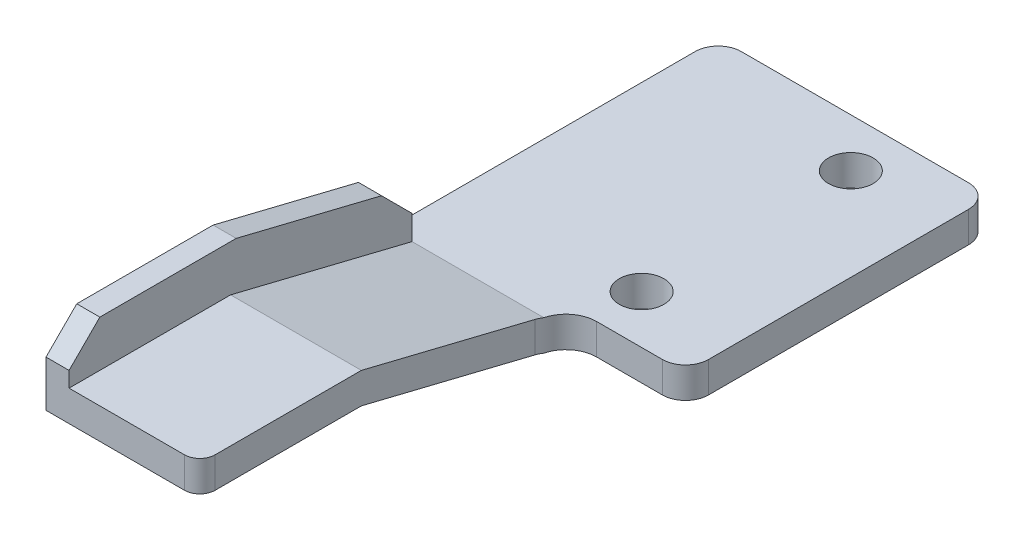
SolidWorks part; units mm, degrees
ref_plane "Front Plane" through (0, 0, 0) normal (0, 0, 1) x (1, 0, 0)
ref_plane "Top Plane" through (0, 0, 0) normal (0, 1, 0) x (1, 0, 0)
ref_plane "Right Plane" through (0, 0, 0) normal (1, 0, 0) x (0, 0, -1)
sketch "Sketch1" plane through (0, 0, 0) normal (0, 1, 0) x (1, 0, 0)
  line L0 (2.885, 6.8) -> (2.885, -6.8) construction
  line L1 (8.885, 9.95) -> (-8.885, 9.95)
  line L2 (8.885, 9.95) -> (8.885, -9.95)
  line L3 (8.885, -9.95) -> (-8.885, -9.95)
  line L4 (-8.885, 9.95) -> (-8.885, -9.95)
  line L5 (8.885, 9.95) -> (-8.885, -9.95) construction
  line L6 (8.885, -9.95) -> (-8.885, 9.95) construction
  circle A0 centre (2.885, 6.8) radius 1.45
  circle A1 centre (2.885, -6.8) radius 1.45
  point P0 (0, 0)
  point P8 (2.885, 0)
  dimension "D3" = 6
  dimension "D5" = 2.9
  dimension "D1" = 19.9
  dimension "D2" = 13.6
  dimension "D4" = 11.77
extrude "Boss-Extrude1" add sketch "Sketch1" along normal blind 2
sketch "Sketch2" plane through (-8.885, 0, 0) normal (-1, 0, 0) x (0, 0, 1)
  line L0 (9.95, 2) -> (11.45, 2)
  line L1 (11.45, 2) -> (23.25, 4.9)
  line L2 (23.25, 4.9) -> (33.75, 4.9)
  line L3 (9.95, 0) -> (11.45, 0)
  line L4 (11.45, 0) -> (23.25, 2.9)
  line L5 (23.25, 2.9) -> (33.75, 2.9)
  line L6 (33.75, 2.9) -> (33.75, 4.9)
  line L7 (11.45, 2) -> (11.45, 0) construction
  line L8 (23.25, 2.9) -> (23.25, 4.9) construction
  line L9 (-9.95, 0) -> (9.95, 0) construction
  line L10 (9.95, 2) -> (9.95, 0)
  dimension "D1" = 2.9
  dimension "D2" = 2
  dimension "D3" = 13.3
  dimension "D4" = 10.5
  dimension "D5" = 1.5
extrude "Boss-Extrude2" add sketch "Sketch2" against normal blind 10
sketch "Sketch4" plane through (-8.885, 0, 0) normal (-1, 0, 0) x (0, 0, 1)
  line L0 (33.75, 4.9) -> (23.25, 4.9) construction
  line L1 (23.25, 4.9) -> (11.45, 2) construction
  line L2 (33.75, 4.9) -> (23.25, 4.9)
  line L3 (23.25, 4.9) -> (11.45, 2)
  line L6 (33.75, 7.9) -> (22.8868, 7.9)
  line L7 (22.8868, 7.9) -> (11.45, 5.0893)
  line L9 (33.75, 4.9) -> (33.75, 7.9)
  line L11 (-8.8807, 10.0858) -> (11.45, 5.0893) construction
  line L12 (-9.5967, 7.1725) -> (11.45, 2) construction
  line L13 (11.45, 5.0893) -> (11.45, 2)
  dimension "D1" = 3
extrude "Boss-Extrude4" add sketch "Sketch4" against normal blind 1.5
chamfer "Chamfer1" distance 2 angle 45 1 edges at (-8.135, 7.9, 33.75)
chamfer "Chamfer2" distance 1.5 angle 45 1 edges at (-8.135, 5.0893, 11.45)
fillet "Fillet1" radius 1.5 3 edges at (8.885, 1, 9.95) (8.885, 1, -9.95) (-8.885, 1, -9.95)
fillet "Fillet2" radius 1 1 edges at (1.115, 3.9, 33.75)
fillet "Fillet3" radius 2 1 edges at (1.115, 1, 9.95)
